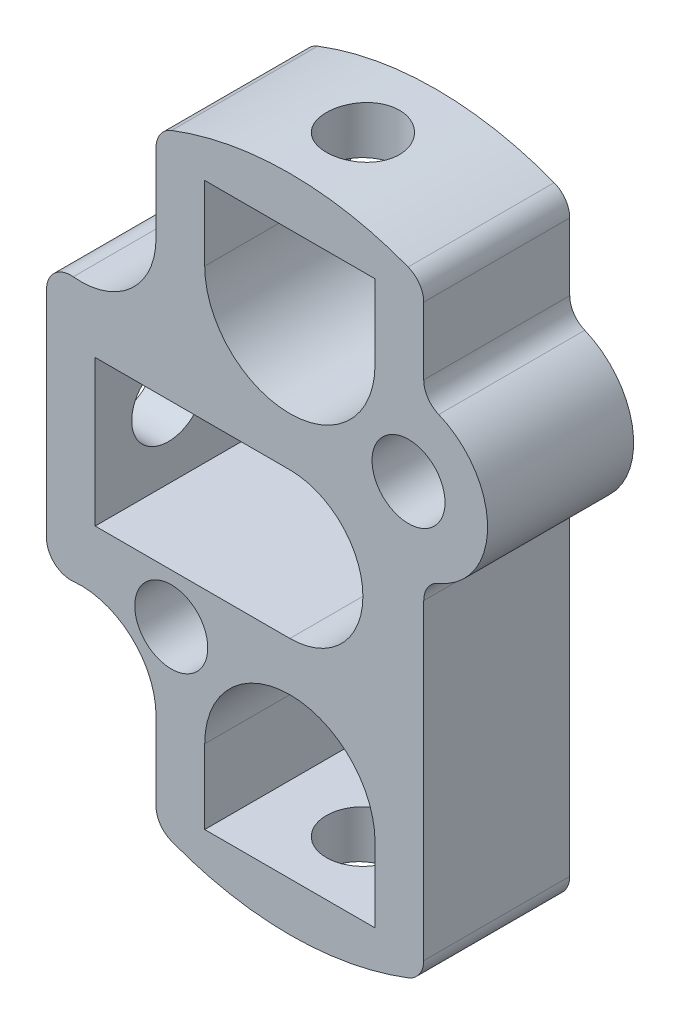
SolidWorks part; units mm, degrees
ref_plane "Plan de face" through (0, 0, 0) normal (0, 0, 1) x (1, 0, 0)
ref_plane "Plan de dessus" through (0, 0, 0) normal (0, 1, 0) x (1, 0, 0)
ref_plane "Plan de droite" through (0, 0, 0) normal (1, 0, 0) x (0, 0, -1)
sketch "Esquisse1" plane through (0, 0, 0) normal (0, 0, 1) x (1, 0, 0)
  line L0 (0, -1000) -> (0, 49000) construction
  line L1 (-3.5, 11.55) -> (3.5, 11.55)
  line L2 (-1000, 0) -> (49000, 0) construction
  line L3 (-3.5, -11.55) -> (3.5, -11.55)
  line L4 (-3.5, 8.5) -> (-3.5, 11.55)
  line L5 (3.5, 8.5) -> (3.5, 11.55)
  line L6 (3.5, -8.5) -> (3.5, -11.55)
  line L7 (-3.5, -8.5) -> (-3.5, -11.55)
  line L8 (-2.8088, -6.4118) -> (-6.3246, -3) construction
  line L9 (0, -3) -> (-8, -3)
  line L10 (0, -3) -> (0, 3) construction
  line L11 (0, 3) -> (-8, 3)
  line L12 (-8, -3) -> (-8, 3)
  line L13 (0, 0) -> (-34820.6125, -35882.0978) construction
  line L14 (5.5, -12.3836) -> (5.5, 12.3836) construction
  line L15 (-10, 4.4244) -> (-10, -4.4244)
  line L16 (-5.5, 11.7155) -> (-5.5, 8.5)
  line L17 (-5.5, -11.7155) -> (-5.5, -8.5)
  line L18 (5.5, 11.7155) -> (5.5, 8.9505)
  line L19 (5.5, 1.0965) -> (5.5, -11.7155)
  circle A0 centre (0, 0) radius 13.55 construction
  circle A1 centre (0, 0) radius 3 construction
  circle A2 centre (0, 0) radius 7 construction
  arc A3 (-3.5, 8.5) -> (3.5, 8.5) centre (0, 8.5) ccw
  arc A4 (-3.5, -8.5) -> (3.5, -8.5) centre (0, -8.5) cw
  arc A5 (0, 3) -> (0, -3) centre (0, 0) cw
  circle A6 centre (-4.8749, -5.0235) radius 1.5
  circle A7 centre (4.8749, 5.0235) radius 1.5
  arc A8 (-5.5, 8.5) -> (-8.9013, 5.4195) centre (-8.5956, 8.5) cw
  arc A9 (-4.8586, 12.649) -> (4.8586, 12.649) centre (0, 0) cw
  arc A10 (-4.8586, -12.649) -> (4.8586, -12.649) centre (0, 0) ccw
  arc A11 (-5.5, -8.5) -> (-8.9013, -5.4195) centre (-8.5956, -8.5) ccw
  arc A12 (-8.9013, -5.4195) -> (-10, -4.4244) centre (-9, -4.4244) cw
  arc A13 (-10, 4.4244) -> (-8.9013, 5.4195) centre (-9, 4.4244) cw
  circle A14 centre (4.8749, 5.0235) radius 3.25 construction
  arc A15 (6.1176, 8.0265) -> (6.1176, 2.0205) centre (4.8749, 5.0235) cw
  arc A16 (6.1176, 2.0205) -> (5.5, 1.0965) centre (6.5, 1.0965) ccw
  arc A17 (5.5, 8.9505) -> (6.1176, 8.0265) centre (6.5, 8.9505) ccw
  arc A18 (5.5, 11.7155) -> (4.8586, 12.649) centre (4.5, 11.7155) ccw
  arc A19 (-5.5, 11.7155) -> (-4.8586, 12.649) centre (-4.5, 11.7155) cw
  arc A20 (4.8586, -12.649) -> (5.5, -11.7155) centre (4.5, -11.7155) ccw
  arc A21 (-4.8586, -12.649) -> (-5.5, -11.7155) centre (-4.5, -11.7155) cw
  point P4 (0, 13.55)
  point P9 (0, 11.55)
  point P21 (0, 5)
  point P22 (0, 3)
  point P41 (6.8467, 0)
  point P48 (-10, 0)
  point P50 (-10, -5.7413)
  point P53 (-10, 5.7413)
  point P56 (5.5, 0)
  point P61 (5.5, 1.8342)
  point P64 (5.5, 8.2128)
  point P69 (-5.5, 12.3836)
  point P75 (-5.5, -12.3836)
  dimension "D1" = 27.1
  dimension "D2" = 6
  dimension "D4" = 14
  dimension "D6" = 8
  dimension "D7" = 2
  dimension "D8" = 3
  dimension "D10" = 3
  dimension "D12" = 1
  dimension "D14" = 6.5
  dimension "D15" = 1
  dimension "D16" = 1
  dimension "D3" = 2
  dimension "D5" = 7
  dimension "D9" = 2
  dimension "D11" = 2
  dimension "D13" = 2
extrude "Boss.-Extru.1" add sketch "Esquisse1" along normal blind 6
sketch "Esquisse2" plane through (0, 11.55, 0) normal (0, -1, 0) x (1, 0, 0)
  line L0 (-3.5, 6) -> (3.5, 0) construction
  circle A0 centre (0, 3) radius 1.5
  dimension "D1" = 3
extrude "Enlèv. mat.-Extru.1" cut sketch "Esquisse2" against normal through all
mirror "Symétrie1" about plane through (0, 0, 0) normal (0, 1, 0) of "Enlèv. mat.-Extru.1"
sketch "Esquisse3" plane through (-8, 0, 0) normal (1, 0, 0) x (0, 0, -1)
  line L0 (-6, 3) -> (0, -3) construction
  circle A0 centre (-3, 0) radius 1.5
  dimension "D1" = 3
extrude "Enlèv. mat.-Extru.2" cut sketch "Esquisse3" against normal through all
